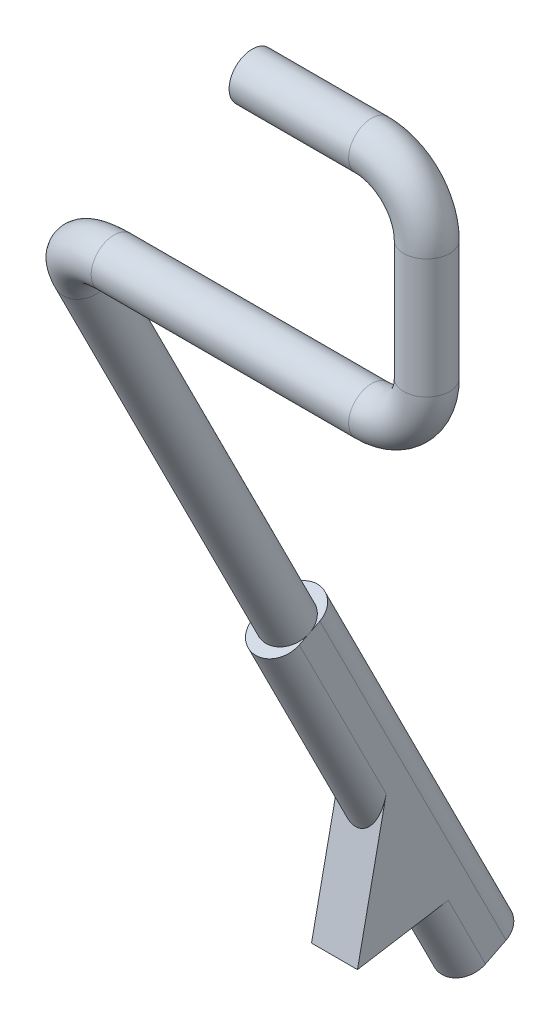
SolidWorks part; units mm, degrees
material "Alloy Steel"
ref_plane "Front Plane" through (0, 0, 0) normal (0, 0, 1) x (1, 0, 0)
ref_plane "Top Plane" through (0, 0, 0) normal (0, 1, 0) x (1, 0, 0)
ref_plane "Right Plane" through (0, 0, 0) normal (1, 0, 0) x (0, 0, -1)
sketch "Sketch1" plane through (0, 0, 0) normal (0, 0, 1) x (1, 0, 0)
  line L0 (-6, 0) -> (-19, 0)
  line L1 (0, -6) -> (0, -25)
  arc A0 (-6, 0) -> (0, -6) centre (-6, -6) cw
  point P6 (0, 0)
  dimension "D3" = 6
  dimension "D1" = 19
  dimension "D2" = 25
sketch3d "3DSketch1"
  line L0 (-6, -25, 0) -> (-34, -25, 0)
  line L1 (0, -25, 0) -> (-40, -25, 0) construction
  line L3 (-40, -30.3582, -2.7) -> (-40, -114.3029, -45)
  line L4 (-40, -25, 0) -> (-40, -25, -45) construction
  line L5 (0, -6, 0) -> (0, -25, 0) construction
  line L6 (0, -6, 0) -> (0, -19, 0)
  line L7 (-6, 0, 0) -> (-19, 0, 0) construction
  line L8 (-6, 0, 0) -> (-19, 0, 0)
  arc A0 (-6, 0, 0) -> (0, -6, 0) centre (-6, -6, 0) ccw construction
  arc A1 (-6, 0, 0) -> (0, -6, 0) centre (-6, -6, 0) ccw
  arc A2 (-34, -25, 0) -> (-40, -30.3582, -2.7) centre (-34, -30.3582, -2.7) ccw
  arc A3 (-6, -25, 0) -> (0, -19, 0) centre (-6, -19, 0) ccw
  point P11 (-6, -6, -6)
  point P13 (-6, -6, -6)
  point P14 (-40, -25, 0)
  point P16 (-34, -33.0582, 2.6582)
  point P19 (0, -25, 0)
  point P21 (-6, -19, 6)
  dimension "D5" = 6
  dimension "D1" = 40
  dimension "D3" = 100
  dimension "D4" = 45
ref_plane "Plane1" through (-19, 0, 0) normal (1, 0, 0) x (0, 0, -1)
sketch "Sketch2" plane through (-19, 0, 0) normal (1, 0, 0) x (0, 0, -1)
  circle A0 centre (0, 0) radius 2.5
  dimension "D1" = 5
sweep "Sweep1" add profiles "Sketch2" path "3DSketch1"
sketch "Sketch3" plane through (0, -109.2404, -55.0466) normal (0, -0.893, -0.45) x (1, 0, 0)
  line L0 (-40, 12.5) -> (-40, 10) construction
  line L1 (-37.5, 12.5) -> (-37.5, 10)
  line L2 (-42.5, 12.5) -> (-42.5, 10)
  arc A0 (-37.5, 12.5) -> (-42.5, 12.5) centre (-40, 12.5) ccw
  arc A1 (-42.5, 10) -> (-37.5, 10) centre (-40, 10) ccw
  circle A2 centre (-40, 11.25) radius 2.5 construction
  circle A3 centre (-40, 11.25) radius 2.5
  point P2 (-40, 11.25)
  circle M6 centre (-40, 11.25) radius 2.5
  dimension "D1" = 2.5
  dimension "D2" = 2.5
extrude "Boss-Extrude1" add sketch "Sketch3" against normal blind 45 contours L1 A0 L2 A3 M6 | L0 A3 M6 | L0 A3 M6 | L2 A1 L1 A3 M6
sketch "Sketch4" plane through (-42.5, 0, 0) normal (-1, 0, 0) x (0, 0, 1)
  line L4 (-39.8337, -106.8281) -> (-29.9633, -108.4327)
  line L5 (-23.6337, -74.6791) -> (-43.8837, -114.8654) construction
  line L6 (-29.9633, -108.4327) -> (-33.0837, -93.4327)
  line L7 (-33.0837, -93.4327) -> (-39.8337, -106.8281)
  line L8 (-43.8837, -114.8654) -> (-46.1163, -113.7404) construction
  dimension "D1" = 15
  dimension "D5" = 15
  dimension "D6" = 9
  dimension "D7" = 10
extrude "Boss-Extrude2" add sketch "Sketch4" against normal up to surface (5 mm away) up to face at (-37.5, -90.1911, -32.85)
